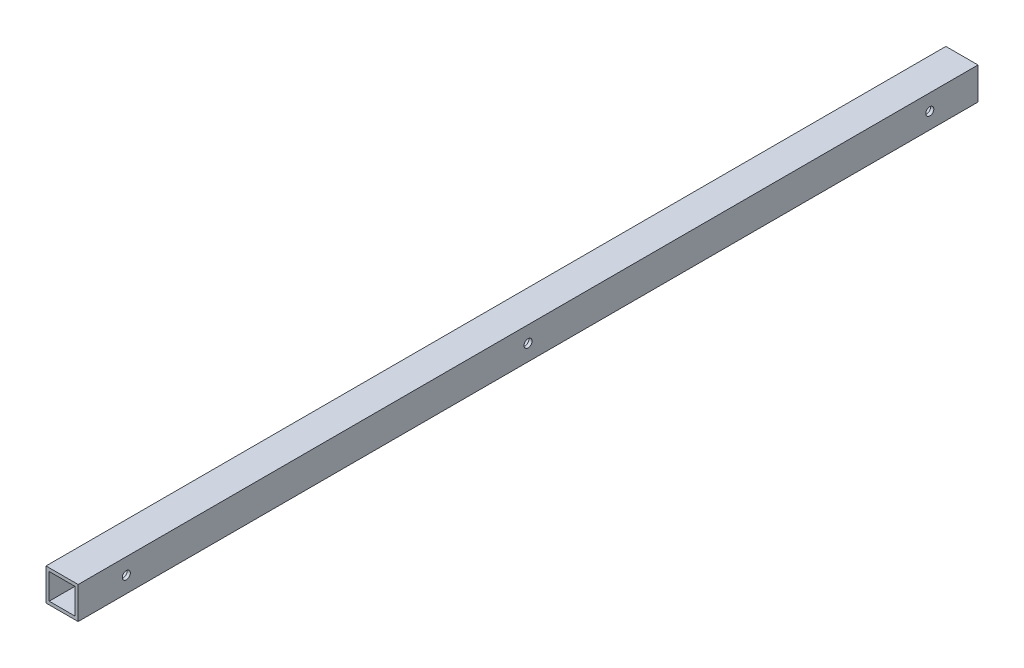
SolidWorks part; units mm, degrees
ref_plane "前视基准面" through (0, 0, 0) normal (0, 0, 1) x (1, 0, 0)
ref_plane "上视基准面" through (0, 0, 0) normal (0, 1, 0) x (1, 0, 0)
ref_plane "右视基准面" through (0, 0, 0) normal (1, 0, 0) x (0, 0, -1)
sketch "草图1" plane through (0, 0, 0) normal (0, 0, 1) x (1, 0, 0)
  line L1 (-10, 10) -> (10, 10)
  line L2 (-10, 10) -> (-10, -10)
  line L3 (-10, -10) -> (10, -10)
  line L4 (10, 10) -> (10, -10)
  line L5 (-10, 10) -> (10, -10) construction
  line L6 (-10, -10) -> (10, 10) construction
  line L7 (-8, 8) -> (8, 8)
  line L8 (-8, 8) -> (-8, -8)
  line L9 (-8, -8) -> (8, -8)
  line L10 (8, 8) -> (8, -8)
  line L11 (-8, 8) -> (8, -8) construction
  line L12 (-8, -8) -> (8, 8) construction
  point P0 (0, 0)
  point P6 (0, 0)
  dimension "D1" = 20
  dimension "D2" = 20
  dimension "D3" = 16
extrude "凸台-拉伸1" add sketch "草图1" against normal blind 560
sketch "草图2" plane through (10, 0, 0) normal (1, 0, 0) x (0, 0, -1)
  line L0 (560, 10) -> (0, 10) construction
  circle A0 centre (280, 0) radius 2.5
  circle A1 centre (30, 0) radius 2.5
  circle A2 centre (530, 0) radius 2.5
  point P9 (0, 0)
  point P11 (507.4093, 10)
  dimension "D2" = 5
  dimension "D4" = 5
  dimension "D5" = 5
  dimension "D1" = 280
  dimension "D3" = 10
  dimension "D6" = 250
  dimension "D7" = 250
  dimension "D8" = 10
  dimension "D9" = 10
extrude "切除-拉伸1" cut sketch "草图2" against normal blind 20
